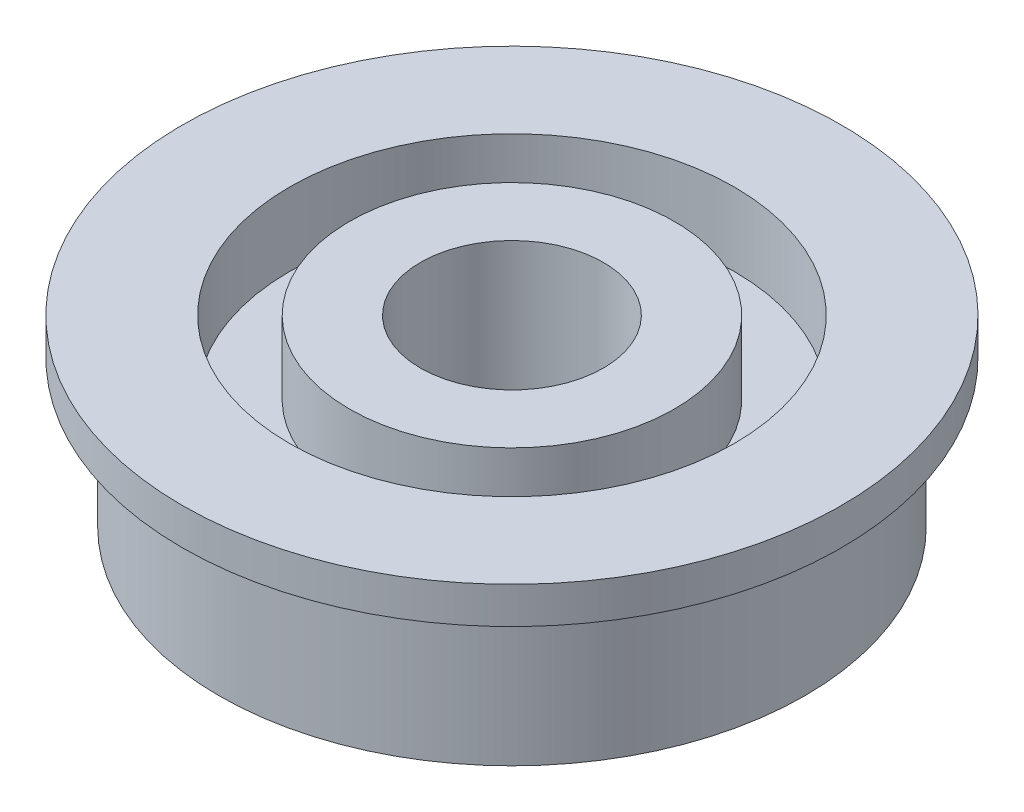
SolidWorks part; units mm, degrees
ref_plane "Front Plane" through (0, 0, 0) normal (0, 0, 1) x (1, 0, 0)
ref_plane "Top Plane" through (0, 0, 0) normal (0, 1, 0) x (1, 0, 0)
ref_plane "Right Plane" through (0, 0, 0) normal (1, 0, 0) x (0, 0, -1)
sketch "Sketch1" plane through (0, 0, 0) normal (0, 1, 0) x (1, 0, 0)
  circle A0 centre (0, 0) radius 8
  circle A1 centre (0, 0) radius 2.5
  dimension "D1" = 16
  dimension "D2" = 5
extrude "Boss-Extrude1" add sketch "Sketch1" along normal blind 4
sketch "Sketch2" plane through (0, 4, 0) normal (0, 1, 0) x (1, 0, 0)
  circle A0 centre (0, 0) radius 9
  circle A1 centre (0, 0) radius 2.5
  dimension "D1" = 18
extrude "Boss-Extrude2" add sketch "Sketch2" along normal blind 1
sketch "Sketch3" plane through (0, 0, 0) normal (0, -1, 0) x (1, 0, 0)
  circle A0 centre (0, 0) radius 4.3551
  circle A1 centre (0, 0) radius 6.0843
extrude "Cut-Extrude1" cut sketch "Sketch3" against normal blind 1
sketch "Sketch4" plane through (0, 5, 0) normal (0, 1, 0) x (1, 0, 0)
  circle A0 centre (0, 0) radius 4.4373
  circle A1 centre (0, 0) radius 6.0701
extrude "Cut-Extrude2" cut sketch "Sketch4" against normal blind 2
